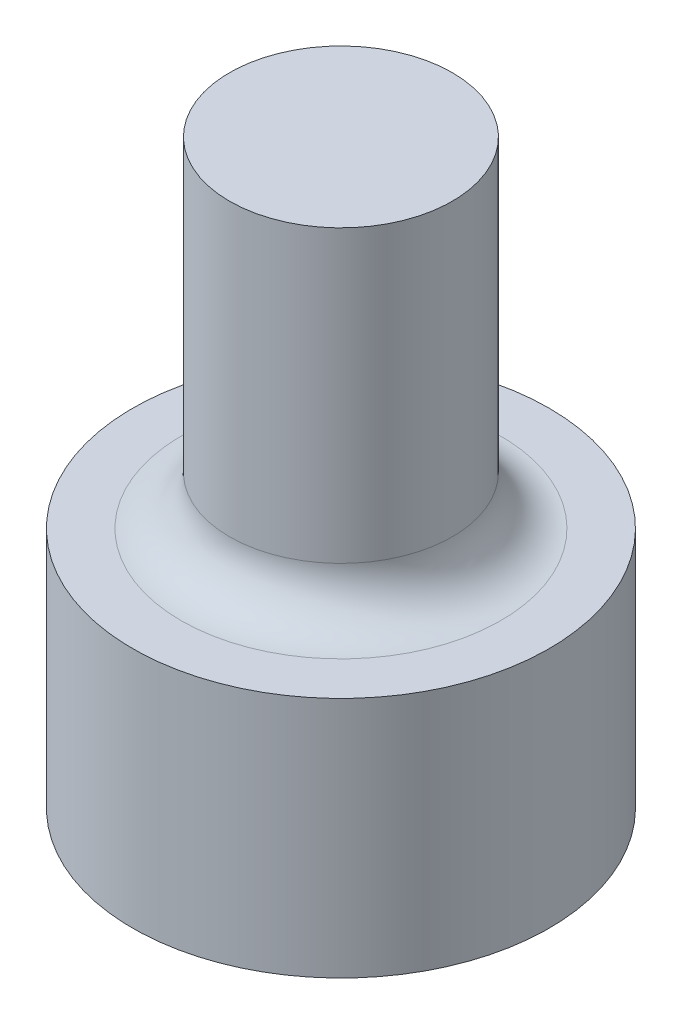
SolidWorks part; units mm, degrees
ref_plane "Front Plane" through (0, 0, 0) normal (0, 0, 1) x (1, 0, 0)
ref_plane "Top Plane" through (0, 0, 0) normal (0, 1, 0) x (1, 0, 0)
ref_plane "Right Plane" through (0, 0, 0) normal (1, 0, 0) x (0, 0, -1)
sketch "Sketch6" plane through (0, 0, 0) normal (0, 1, 0) x (1, 0, 0)
  circle A0 centre (0, 0) radius 5.461
  dimension "D1" = 10.922
extrude "Boss-Extrude4" add sketch "Sketch6" along normal blind 15.24
sketch "Sketch7" plane through (0, 15.24, 0) normal (0, 1, 0) x (1, 0, 0)
  circle A0 centre (0, 0) radius 2.921
  dimension "D1" = 5.842
extrude "Cut-Extrude2" cut sketch "Sketch7" against normal blind 8.89 flip side to cut
sketch "Sketch8" plane through (0, 0, 0) normal (0, -1, 0) x (1, 0, 0)
  circle A0 centre (0, 0) radius 4.8895
  dimension "D1" = 9.779
extrude "Cut-Extrude3" cut sketch "Sketch8" against normal blind 5.08
fillet "Fillet2" radius 1.27 1 edges at (0, 6.35, 2.921)
